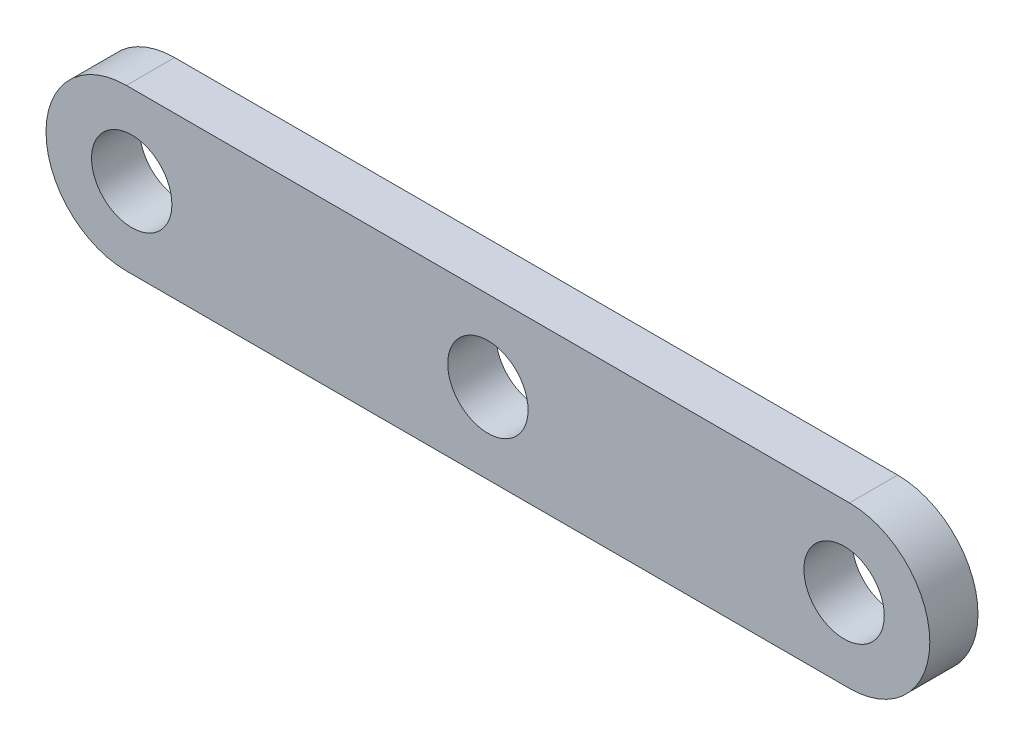
SolidWorks part; units mm, degrees
ref_plane "Plano frontal" through (0, 0, 0) normal (0, 0, 1) x (1, 0, 0)
ref_plane "Plano superior" through (0, 0, 0) normal (0, 1, 0) x (1, 0, 0)
ref_plane "Plano direito" through (0, 0, 0) normal (1, 0, 0) x (0, 0, -1)
sketch "Esboço1" plane through (0, 0, 0) normal (0, 0, 1) x (1, 0, 0)
  line L0 (-65.2183, 0) -> (-20.2183, 0) construction
  line L1 (-65.2183, 5) -> (-20.2183, 5)
  line L2 (-65.2183, -5) -> (-20.2183, -5)
  arc A0 (-65.2183, 5) -> (-65.2183, -5) centre (-65.2183, 0) ccw
  arc A1 (-20.2183, -5) -> (-20.2183, 5) centre (-20.2183, 0) ccw
  circle A2 centre (-64.8844, 0) radius 2.5
  circle A3 centre (-42.7183, 0) radius 2.5
  circle A4 centre (-20.5522, 0) radius 2.5
  point P3 (-42.7183, 0)
extrude "Ressalto-extrusão1" add sketch "Esboço1" along normal blind 3
